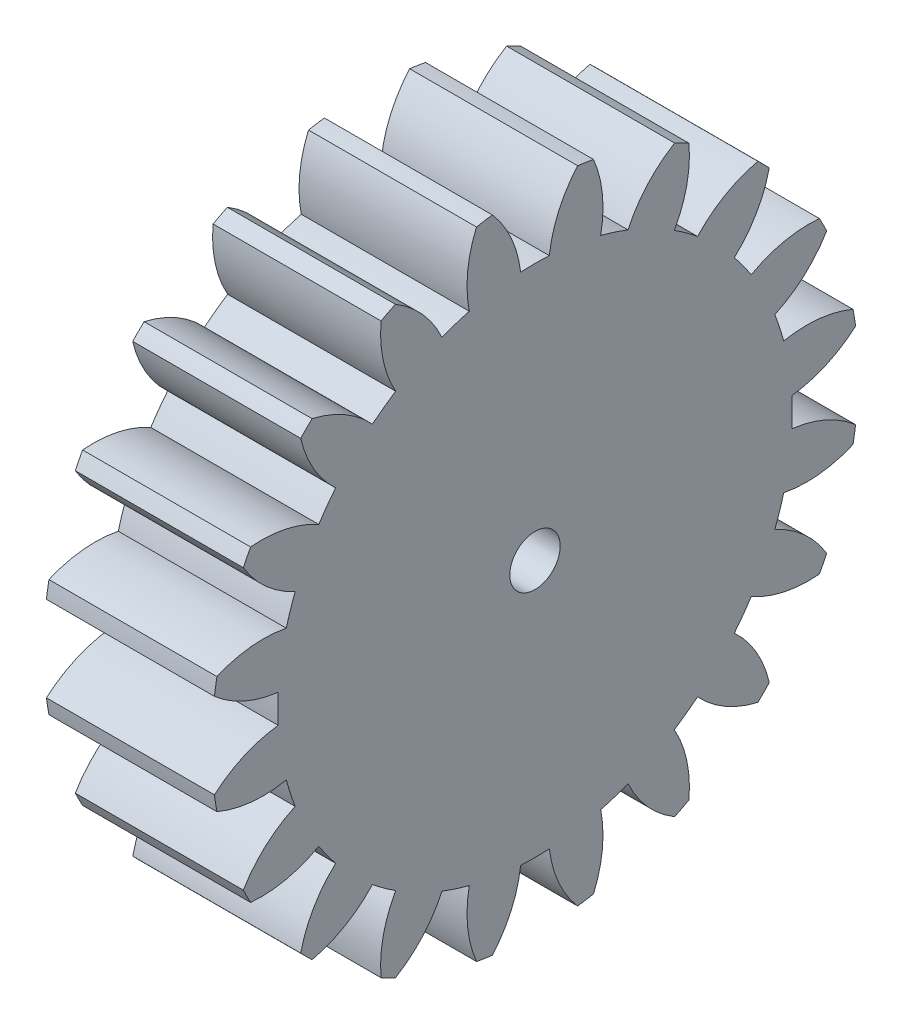
SolidWorks part; units mm, degrees
ref_plane "Plane1" through (0, 0, 0) normal (0, 0, 1) x (1, 0, 0)
ref_plane "Plane2" through (0, 0, 0) normal (0, 1, 0) x (1, 0, 0)
ref_plane "Plane3" through (0, 0, 0) normal (1, 0, 0) x (0, 0, -1)
sketch "HoldingSke" plane through (0, 0, 0) normal (0, 1, 0) x (1, 0, 0)
  line L0 (0, 0) -> (0.537, -0.1954)
  line L1 (-15, 0) -> (100, 0) construction
  line L2 (0, 0) -> (-2.1039, 2.3779)
  line L3 (0, 0) -> (-11.863, 4.5341)
  line L4 (0, 0) -> (8.1152, 2.9537)
  line L5 (0, 0) -> (-46.8476, -17.4728)
  line L6 (0, 0) -> (-8.2896, -5.593)
  line L7 (-2.1039, 2.3779) -> (8.6586, 51.2059)
  line L8 (-76.2, 54.61) -> (-75.7, 54.61)
  line L9 (-71.009, 38.7566) -> (-53.1078, 45.2721)
  line L10 (-76.2, 71.12) -> (104.1128, 71.12)
  line L11 (0, 0) -> (-10, 0)
  line L12 (-76.2, 101.6) -> (-76.147, 101.6)
  line L13 (24.9733, 27.94) -> (52.9518, 28.4284)
  line L14 (24.9733, 27.94) -> (24.9743, 27.94)
  line L15 (24.9733, 27.94) -> (100.4006, 29.5858)
  line L16 (-63.627, -1.75) -> (-12.827, -1.75)
  circle A0 centre (0, 0) radius 1.5
  circle A1 centre (0, 0) radius 15.3115
  circle A2 centre (0, 0) radius 37.5
  circle A3 centre (0, 0) radius 1.5
  dimension "MHD" = 30.623
  dimension "Hub_dia" = 75
  dimension "Bore" = 3
  dimension "MBD" = 3
  dimension "Num_teeth" = 20
  dimension "Pitch" = 0.5714
  dimension "Overall_len" = 50
  dimension "Show_teeth" = 20
  dimension "Thickness" = 10
  dimension "OAL" = 50.0001
  dimension "T_dim" = 0.5
  dimension "Ap" = 20
  dimension "H" = 19.05
  dimension "Pitch_radius" = 180.3128
  dimension "Width" = 10
  dimension "Backlash" = 0.053
  dimension "Addendum_fac" = 1
  dimension "Dedendum_fac" = 1.25
  dimension "Clearance_fac" = 0.25
  dimension "Dedendum_add" = 0.001
  dimension "Module" = 1.75
sketch "BasProSke" plane through (0, 0, 0) normal (0, 1, 0) x (1, 0, 0)
  line L0 (-10, 0) -> (60, 0) construction
  line L1 (0, 0) -> (0, 19.25)
  line L2 (0, 0) -> (10, 0)
  line L3 (10, 0) -> (10, 19.25)
  line L4 (10, 19.25) -> (0, 19.25)
  dimension "Thickness" = 10
  dimension "Diameter" = 38.5
revolve "Base-Revolve" add sketch "BasProSke" angle 360 about L0
sketch "TooCutSke" plane through (0, 0, 0) normal (1, 0, 0) x (0, 0, -1)
  line L1 (0, 0) -> (0, 107) construction
  line L2 (0, 0) -> (-1.4657, 17.4385) construction
  line L3 (0, 0) -> (-5.4605, 34.4765) construction
  line L4 (-1.4657, 17.4385) -> (-2.7303, 17.2382) construction
  arc A0 (0.8543, 15.2877) -> (-0.8543, 15.2877) centre (0, 0) ccw
  arc A1 (2.558, 19.1049) -> (-2.558, 19.1049) centre (0, 0) ccw
  circle A2 centre (0, 0) radius 17.5 construction
  circle A3 centre (0, 0) radius 16.4446 construction
  arc A4 (-0.8543, 15.2877) -> (-2.558, 19.1049) centre (-7.8067, 14.4734) ccw
  arc A5 (2.558, 19.1049) -> (0.8543, 15.2877) centre (7.8067, 14.4734) ccw
  dimension "Root_dia" = 30.623
  dimension "Overcut_dia" = 38.5508
  dimension "Pitch_dia" = 35
  dimension "Base_dia" = 32.8892
  dimension "Flank_rad" = 7
  dimension "Half_ang" = 9
  dimension "Half_CT" = 1.2803
extrude "ToothCut" cut sketch "TooCutSke" along normal through all
fillet "Breaks" [suppressed] radius 0.035
fillet "RootFillets" [suppressed] radius 0.4385
pattern_circular "TeethCuts" count 20 every 18 about axis through (-10, 0, 0) along (1, 0, 0) of "ToothCut", "RootFillets", "Breaks"
sketch "HubNeaOneSke" plane through (0, 0, 0) normal (-1, 0, 0) x (0, 0, 1)
  circle A0 centre (0, 0) radius 15.3115
  dimension "Diameter" = 30.623
extrude "HubNearOne" [suppressed] add sketch "HubNeaOneSke" along normal blind 40.0001
sketch "HubNeaBotSke" plane through (0, 0, 0) normal (-1, 0, 0) x (0, 0, 1)
  circle A0 centre (0, 0) radius 15.3115
  dimension "Diameter" = 30.623
extrude "HubNearBoth" [suppressed] add sketch "HubNeaBotSke" along normal blind 20
ref_plane "FarPln" through (10, 0, 0) normal (1, 0, 0) x (0, 0, -1)
sketch "HubFarSke" plane through (10, 0, 0) normal (1, 0, 0) x (0, 0, -1)
  circle A0 centre (0, 0) radius 15.3115
  dimension "Diameter" = 30.623
extrude "HubFar" [suppressed] add sketch "HubFarSke" along normal blind 20
sketch "BorSke" plane through (0, 0, 0) normal (1, 0, 0) x (0, 0, -1)
  circle A0 centre (0, 0) radius 1.5
  dimension "Diameter" = 3
extrude "Bore" cut sketch "BorSke" along normal mid plane 100.0001
sketch "KeySke" plane through (0, 0, 0) normal (1, 0, 0) x (0, 0, -1)
  line L0 (-0.6, 0) -> (-0.6, 2)
  line L1 (-0.6, 2) -> (0.6, 2)
  line L2 (0.6, 2) -> (0.6, 0)
  line L3 (0, 0) -> (0, 34) construction
  line L4 (-0.6, 0) -> (0.6, 0)
  dimension "Offset" = 2
  dimension "Width" = 1.2
extrude "Keyway" [suppressed] cut sketch "KeySke" along normal mid plane 100.0001
pattern_circular "Keyway2" [suppressed] count 2 every 90 about axis through (-10, 0, 0) along (1, 0, 0)
equation "' \"Module@HoldingSke\" = 6.35"
equation "' \"Num_teeth@HoldingSke\" = 12"
equation "' \"Ap@HoldingSke\" =  20"
equation "' \"Ap@HoldingSke\" = 20"
equation "' \"Width@HoldingSke\" = 0.5 * 25.4"
equation "' \"Hub_dia@HoldingSke\"= 1 * 25.4"
equation "' \"Hub_dia@HoldingSke\" = 1 * 25.4"
equation "' \"Overall_len@HoldingSke\" = 1.0 * 25.4"
equation "' \"Bore@HoldingSke\" = 0.75 * 25.4"
equation "' \"T_dim@HoldingSke\" = 0.1 * 25.4"
equation "' \"Width@KeySke\" = 0.25 * 25.4"
equation "' \"Show_teeth@HoldingSke\" = 13"
equation "' \"Backlash@HoldingSke\" = 0.009 * 25.4"
equation "' \"Addendum_fac@HoldingSke\" = 1.0"
equation "' \"Dedendum_fac@HoldingSke\" = 1.25"
equation "' \"Dedendum_add@HoldingSke\" = 0.00005 * 25.4"
equation "' \"Clearance_fac@HoldingSke\" = 0.25"
equation "\"Pitch@HoldingSke\" = 1 / \"Module@HoldingSke\""
equation "\"Overcut_dia@TooCutSke\" = (\"Num_teeth@HoldingSke\" + 2 * \"Addendum_fac@HoldingSke\") / \"Pitch@HoldingSke\" + 0.002 * 25.4"
equation "\"Pitch_dia@TooCutSke\" = \"Num_teeth@HoldingSke\" / \"Pitch@HoldingSke\""
equation "\"Base_dia@TooCutSke\" = \"Num_teeth@HoldingSke\" / \"Pitch@HoldingSke\" * cos((\"Ap@HoldingSke\"  * 3.14159265 / 180))"
equation "\"Root_dia@TooCutSke\" = (\"Num_teeth@HoldingSke\" + 2) / \"Pitch@HoldingSke\" - 2 * (\"Addendum_fac@HoldingSke\" + \"Dedendum_fac@HoldingSke\") / \"Pitch@HoldingSke\" - \"Dedendum_add@HoldingSke\" * 2"
equation "\"Half_ang@TooCutSke\" = 180 / \"Num_teeth@HoldingSke\""
equation "\"Half_CT@TooCutSke\" = \"Num_teeth@HoldingSke\" / \"Pitch@HoldingSke\" * sin((3.14159265 / 2 / \"Num_teeth@HoldingSke\")) / 2 - 7 * \"Backlash@HoldingSke\" / 4"
equation "\"Flank_rad@TooCutSke\" = \"Num_teeth@HoldingSke\" / \"Pitch@HoldingSke\" / 5"
equation "\"Radius@RootFillets\" = \"Clearance_fac@HoldingSke\" / \"Pitch@HoldingSke\" + \"Dedendum_add@HoldingSke\""
equation "\"Break_rad@Breaks\" = 0.02 / \"Pitch@HoldingSke\""
equation "\"Thickness@HoldingSke\" = \"Width@HoldingSke\""
equation "\"OAL@HoldingSke\" = \"Thickness@HoldingSke\""
equation "\"MHD@HoldingSke\" = (\"Num_teeth@HoldingSke\" + 2) / \"Pitch@HoldingSke\" - 2 * (\"Addendum_fac@HoldingSke\" + \"Dedendum_fac@HoldingSke\")  / \"Pitch@HoldingSke\" - \"Dedendum_add@HoldingSke\" * 2"
equation "\"MBD@HoldingSke\" = (\"Num_teeth@HoldingSke\" + 2) / \"Pitch@HoldingSke\" - 2 * (\"Addendum_fac@HoldingSke\" + \"Dedendum_fac@HoldingSke\")  / \"Pitch@HoldingSke\" - \"Dedendum_add@HoldingSke\" * 2 - 0.002 * 25.4"
equation "\"MHD@HoldingSke\" = ((sgn( \"MHD@HoldingSke\" - \"Hub_dia@HoldingSke\" )-1)*( \"MHD@HoldingSke\" - \"Hub_dia@HoldingSke\" ))/-2+ \"Hub_dia@HoldingSke\""
equation "\"MBD@HoldingSke\" = ((sgn( \"MBD@HoldingSke\" - \"Bore@HoldingSke\" )-1)*( \"MBD@HoldingSke\" - \"Bore@HoldingSke\" ))/-2+ \"Bore@HoldingSke\""
equation "\"OAL@HoldingSke\" = ((sgn( \"OAL@HoldingSke\" - \"Overall_len@HoldingSke\" )+1)*( \"OAL@HoldingSke\" - \"Overall_len@HoldingSke\" ))/2 + \"Overall_len@HoldingSke\" + 0.000002 * 25.4"
equation "\"Num_teeth@TeethCuts\" = int( \"Show_teeth@HoldingSke\" ) + 1"
equation "\"Num_teeth@TeethCuts\" = ((sgn( \"Num_teeth@TeethCuts\" - \"Num_teeth@HoldingSke\" )-1)*( \"Num_teeth@TeethCuts\" - \"Num_teeth@HoldingSke\" ))/-2+ \"Num_teeth@HoldingSke\""
equation "\"Num_teeth@TeethCuts\" = ((sgn( \"Num_teeth@TeethCuts\" - 2.0)+1)*( \"Num_teeth@TeethCuts\" - 2.0))/2 +2.0"
equation "\"Angle@TeethCuts\" = 360.0 / \"Num_teeth@HoldingSke\""
equation "\"Diameter@BasProSke\" = (\"Num_teeth@HoldingSke\" + 2 * \"Addendum_fac@HoldingSke\") / \"Pitch@HoldingSke\""
equation "\"Thickness@BasProSke\"  = \"Thickness@HoldingSke\""
equation "' \"Fillet_rad@BasProSke\" =  \"Thickness@HoldingSke\" * 0.05"
equation "' \"Fillet_rad@BasProSke\" = \"Thickness@HoldingSke\" * 0.05"
equation "\"MHD@HoldingSke\" = ((sgn( \"MHD@HoldingSke\" - \"Root_dia@TooCutSke\" )-1)*( \"MHD@HoldingSke\" - \"Root_dia@TooCutSke\" ))/-2+ \"Root_dia@TooCutSke\""
equation "\"Diameter@HubNeaOneSke\" = \"MHD@HoldingSke\""
equation "\"Length@HubNearOne\" = \"OAL@HoldingSke\" - \"Thickness@BasProSke\""
equation "\"Diameter@HubNeaBotSke\" = \"MHD@HoldingSke\""
equation "\"Length@HubNearBoth\" = ( \"OAL@HoldingSke\" - \"Thickness@BasProSke\" ) / 2.0"
equation "\"Thickness@FarPln\" = \"Thickness@BasProSke\""
equation "\"Diameter@HubFarSke\" = \"MHD@HoldingSke\""
equation "\"Length@HubFar\" = ( \"OAL@HoldingSke\" - \"Thickness@BasProSke\" ) / 2.0"
equation "\"Diameter@BorSke\" = \"MBD@HoldingSke\""
equation "\"D1@Bore\" = \"OAL@HoldingSke\" * 2.0"
equation "\"D1@Keyway\" = \"OAL@HoldingSke\" * 2.0"
equation "\"Offset@KeySke\" = \"T_dim@HoldingSke\" + \"MBD@HoldingSke\" / 2.0"
